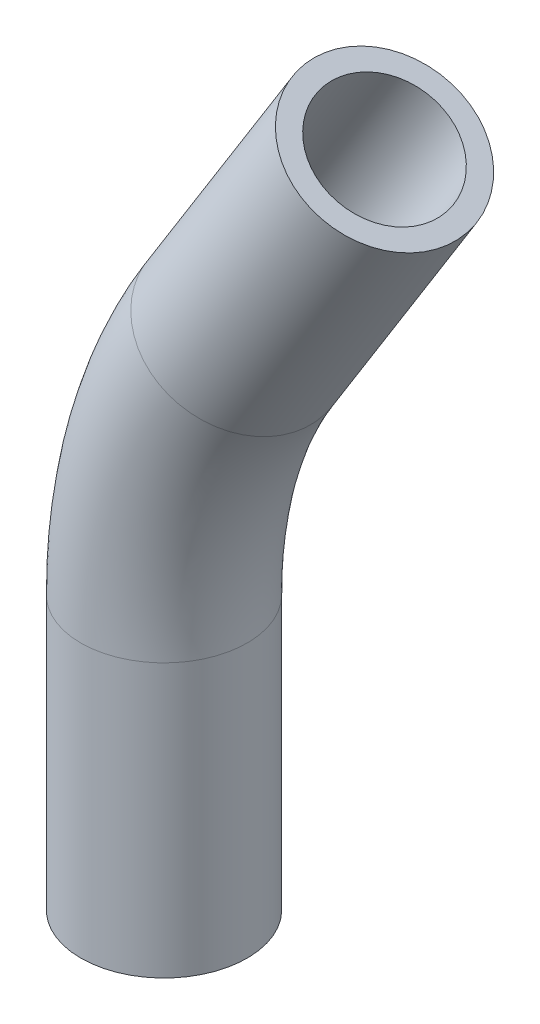
SolidWorks part; units mm, degrees
ref_plane "Front Plane" through (0, 0, 0) normal (0, 0, 1) x (1, 0, 0)
ref_plane "Top Plane" through (0, 0, 0) normal (0, 1, 0) x (1, 0, 0)
ref_plane "Right Plane" through (0, 0, 0) normal (1, 0, 0) x (0, 0, -1)
sketch "Sketch1" plane through (0, 0, 0) normal (0, 0, 1) x (1, 0, 0)
  line L0 (0, 0) -> (0, 13.1181)
  line L1 (3.6468, 25.8362) -> (10.5984, 36.961)
  arc A0 (0, 13.1181) -> (3.6468, 25.8362) centre (24, 13.1181) cw
  point P6 (0, 20)
  dimension "D3" = 24
  dimension "D1" = 20
  dimension "D2" = 20
  dimension "D4" = 148
sketch "Sketch2" plane through (0, 0, 0) normal (0, 1, 0) x (1, 0, 0)
  circle A0 centre (0, 0) radius 4
  circle A1 centre (0, 0) radius 3
  dimension "D1" = 6
  dimension "D2" = 8
sweep "Sweep1" add profiles "Sketch2" path "Sketch1"
